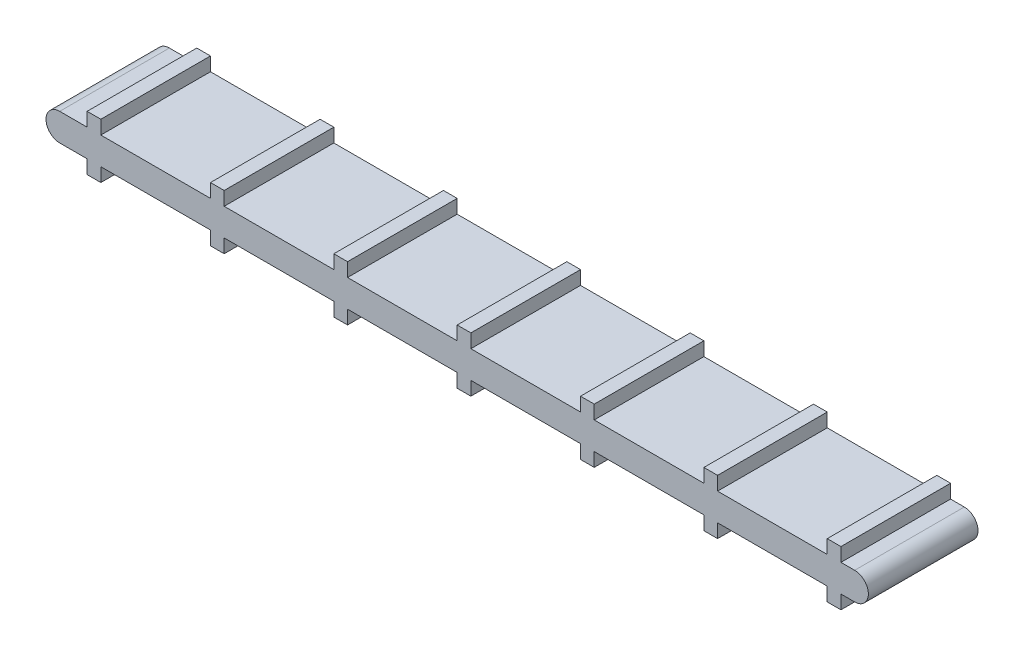
SolidWorks part; units mm, degrees
ref_plane "Front Plane" through (0, 0, 0) normal (0, 0, 1) x (1, 0, 0)
ref_plane "Top Plane" through (0, 0, 0) normal (0, 1, 0) x (1, 0, 0)
ref_plane "Right Plane" through (0, 0, 0) normal (1, 0, 0) x (0, 0, -1)
sketch "Sketch1" plane through (0, 0, 0) normal (0, 1, 0) x (1, 0, 0)
  line L1 (0, 0) -> (-300, 0)
  line L2 (0, 0) -> (0, 40)
  line L3 (0, 40) -> (-300, 40)
  line L4 (-300, 0) -> (-300, 40)
  point P5 (0, 0)
  point P6 (0, 0)
  point P7 (0, 0)
  point P8 (0, 0)
  dimension "D1" = 40
  dimension "D2" = 300
extrude "Boss-Extrude1" add sketch "Sketch1" along normal blind 10
sketch "Sketch2" plane through (0, 0, -40) normal (0, 0, -1) x (-1, 0, 0)
  line L0 (0, 5) -> (5, 5)
  line L1 (0, 10) -> (0, 0) construction
  line L2 (5, 10) -> (0, 10)
  line L3 (0, 10) -> (0, 0)
  line L4 (0, 0) -> (5, 0)
  line L5 (5, 0) -> (5, 10)
  circle A0 centre (5, 5) radius 5
  line M3 (0, 0) -> (300, 0)
  line M5 (300, 10) -> (0, 10)
  line M6 (0, 10) -> (0, 0)
extrude "Cut-Extrude1" cut sketch "Sketch2" against normal blind 40 contours A0 M5 M6 | A0 M6 M3
sketch "Sketch4" plane through (0, 0, -40) normal (0, 0, -1) x (-1, 0, 0)
  line L0 (300, 5) -> (295, 5)
  line L1 (300, 10) -> (300, 0) construction
  line L2 (295, 10) -> (300, 10)
  line L3 (300, 10) -> (300, 0)
  line L4 (300, 0) -> (295, 0)
  circle A0 centre (295, 5) radius 5
  line M4 (5, 0) -> (300, 0)
  line M5 (300, 0) -> (300, 10)
  line M6 (300, 10) -> (5, 10)
extrude "Cut-Extrude2" cut sketch "Sketch4" against normal blind 40 contours A0 M5 M6 | A0 M4 M5
sketch "Sketch5" plane through (0, 10, 0) normal (0, 1, 0) x (1, 0, 0)
  line L0 (-150, 40) -> (-150, 0)
  line L1 (-295, 40) -> (-5, 40)
  line L2 (-295, 40) -> (-295, 0)
  line L3 (-295, 0) -> (-5, 0)
  line L4 (-5, 40) -> (-5, 0)
  line L5 (-150, 40) -> (-5, 40)
  line L6 (-150, 40) -> (-145, 40)
  line L7 (-77.5, 0) -> (-5, 0)
  line L8 (-145, 40) -> (-105, 40)
  line L9 (-41.25, 40) -> (-5, 40)
  line L10 (-145, 40) -> (-150, 40)
  line L11 (-77.5, 40) -> (-41.25, 40)
  line L12 (-145, 40) -> (-145, 0)
  line L13 (-145, 0) -> (-150, 0)
  line L14 (-150, 40) -> (-150, 0)
  line L15 (-105, 40) -> (-105, 0)
  line L16 (-105, 40) -> (-100, 40)
  line L17 (-5, 40) -> (-295, 40) construction
  line L18 (-100, 40) -> (-100, 0)
  line L19 (-105, 40) -> (-100, 40)
  line L20 (-105, 40) -> (-100, 40)
  line L21 (-105, 40) -> (-105, 0)
  line L22 (-105, 0) -> (-100, 0)
  line L23 (-100, 40) -> (-100, 0)
  line L24 (-102.5, 40) -> (-102.5, 0)
  line L25 (-60, 0) -> (-55, 0)
  line L26 (-55, 40) -> (-55, 0)
  line L27 (-60, 40) -> (-55, 40)
  line L28 (-60, 40) -> (-60, 0)
  line L29 (-60, 40) -> (-55, 40)
  line L30 (-57.5, 40) -> (-57.5, 0)
  line L31 (-10, 0) -> (-15, 0)
  line L32 (-15, 40) -> (-15, 0)
  line L33 (-10, 40) -> (-15, 40)
  line L34 (-10, 40) -> (-10, 0)
  line L35 (-150, 40) -> (-145, 40)
  line L36 (-147.5, 40) -> (-147.5, 0)
  line L37 (-285, 40) -> (-285, 0)
  line L38 (-285, 40) -> (-280, 40)
  line L39 (-280, 40) -> (-280, 0)
  line L40 (-285, 0) -> (-280, 0)
  line L41 (-235, 40) -> (-235, 0)
  line L42 (-235, 40) -> (-240, 40)
  line L43 (-240, 40) -> (-240, 0)
  line L44 (-235, 0) -> (-240, 0)
  line L45 (-190, 0) -> (-195, 0)
  line L46 (-195, 40) -> (-195, 0)
  line L47 (-190, 40) -> (-195, 40)
  line L48 (-190, 40) -> (-190, 0)
  line M22 (-295, 0) -> (-5, 0)
  dimension "D1" = 5
  dimension "D2" = 5
  dimension "4cm" = 40
  dimension "D3" = 40
  dimension "D4" = 13.75
  dimension "D5" = 17.5
  dimension "D6" = 40
extrude "Boss-Extrude3" add sketch "Sketch5" along normal blind 5 contours L39 L1 L37 L3 | L48 L1 L46 M22 | L36 L35 L0 M22 | L5 L36 L13 L12 | L24 L20 L15 M22 | L5 L24 L22 L18 | L30 L29 L28 L7 | L11 L30 L25 L26 | L34 L9 L32 L7 | L41 L44 L43 L42
ref_plane "Plane1" through (0, 5, 0) normal (0, 1, 0) x (1, 0, 0)
mirror "Mirror2" about plane through (0, 5, 0) normal (0, 1, 0) of "Boss-Extrude3"
